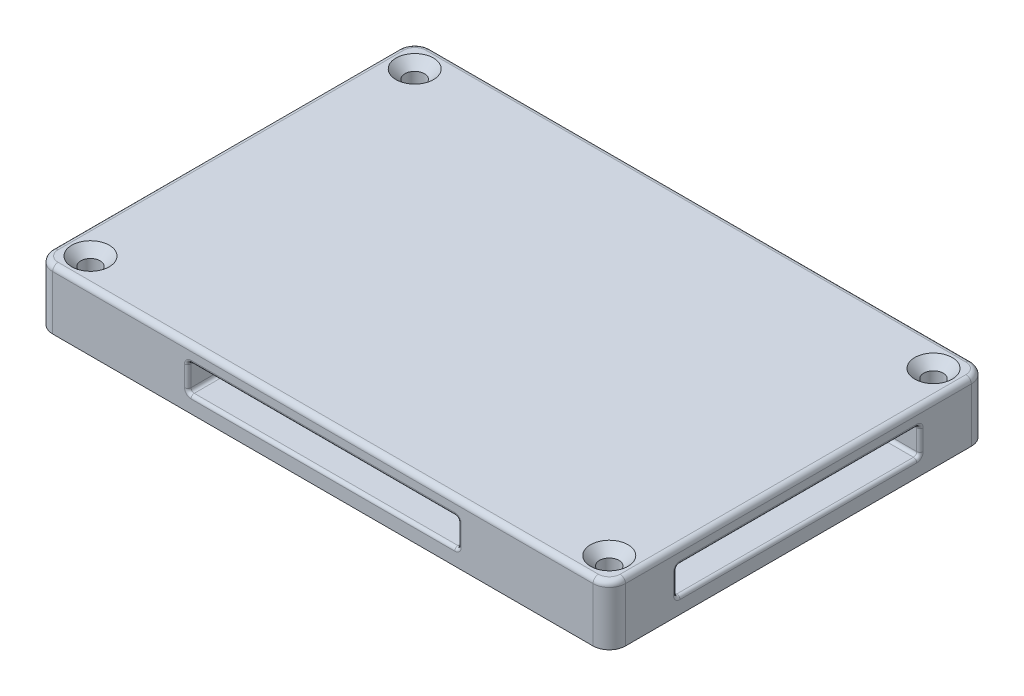
SolidWorks part; units mm, degrees
ref_plane "Alzado" through (0, 0, 0) normal (0, 0, 1) x (1, 0, 0)
ref_plane "Planta" through (0, 0, 0) normal (0, 1, 0) x (1, 0, 0)
ref_plane "Vista lateral" through (0, 0, 0) normal (1, 0, 0) x (0, 0, -1)
sketch "Croquis1" plane through (0, 0, 0) normal (0, 1, 0) x (1, 0, 0)
  line L1 (0, 0) -> (106, 0)
  line L2 (0, 0) -> (0, 70)
  line L3 (0, 70) -> (106, 70)
  line L4 (106, 0) -> (106, 70)
  dimension "D1" = 106
  dimension "D2" = 70
extrude "Saliente-Extruir1" add sketch "Croquis1" along normal blind 11
sketch "Croquis2" plane through (0, 0, 0) normal (0, 0, 1) x (1, 0, 0)
  line L0 (0, 0) -> (0, 3) construction
  line L1 (0, 11) -> (0, 0) construction
  line L2 (0, 3) -> (28, 3) construction
  line L4 (28, 3) -> (78, 3)
  line L5 (28, 3) -> (28, 8)
  line L6 (28, 8) -> (78, 8)
  line L7 (78, 3) -> (78, 8)
  dimension "D1" = 3
  dimension "D2" = 28
  dimension "D3" = 50
  dimension "D4" = 5
extrude "Cortar-Extruir1" cut sketch "Croquis2" against normal through all
sketch "Croquis3" plane through (106, 0, 0) normal (1, 0, 0) x (0, 0, -1)
  line L0 (0, 0) -> (0, 3) construction
  line L1 (0, 3) -> (12.5, 3) construction
  line L3 (12.5, 3) -> (57.5, 3)
  line L4 (12.5, 3) -> (12.5, 8)
  line L5 (12.5, 8) -> (57.5, 8)
  line L6 (57.5, 3) -> (57.5, 8)
  dimension "D1" = 45
  dimension "D2" = 12.5
  dimension "D3" = 5
extrude "Cortar-Extruir2" cut sketch "Croquis3" against normal through all
fillet "Redondeo1" radius 3 4 edges at (0, 5.5, 0) (0, 5.5, -70) (106, 5.5, -70) (106, 5.5, 0)
sketch "Croquis5" plane through (0, 11, 0) normal (0, 1, 0) x (1, 0, 0)
  line L0 (5, 0) -> (5, 5) construction
  line L1 (3, 0) -> (103, 0) construction
  line L2 (5, 5) -> (0, 5) construction
  line L3 (0, 67) -> (0, 3) construction
  line L4 (53, 0) -> (53, 70) construction
  line L5 (103, 70) -> (3, 70) construction
  line L6 (0, 35) -> (106, 35) construction
  line L7 (106, 3) -> (106, 67) construction
  point P15 (101, 5)
  point P16 (5, 5)
  point P17 (101, 65)
  point P18 (5, 65)
  dimension "D1" = 5
  dimension "D2" = 5
hole_wizard "Avellanado para tornillo con cabeza avellanada de clavija hexagonal de M32" positions "Croquis11" profile "Croquis12" countersink size "M3" standard "DIN" end condition through all
sketch "Croquis11" plane through (0, 11, 0) normal (0, 1, 0) x (1, 0, 0)
  point P0 (5, 65)
  point P3 (101, 65)
  point P6 (101, 5)
  point P9 (5, 5)
sketch "Croquis12" plane through (5, 11, -65) normal (1, 0, 0) x (0, 0, 1)
  line L0 (0, 0) -> (0, 11)
  line L1 (0, 11) -> (1.8, 11)
  line L2 (1.8, 11) -> (1.8, 1.67)
  line L3 (1.8, 1.67) -> (3.47, 0)
  line L5 (3.47, 0) -> (0, 0)
  line L6 (-1.8, 1.67) -> (-3.47, 0) construction
  line L11 (0, -6.35) -> (0, 107.95) construction
  dimension "Diámetro de taladro hasta el siguiente" = 3.6
  dimension "Profundidad de taladro hasta el siguiente" = 11
  dimension "Diámetro de avellanado cercano" = 6.94
  dimension "Ángulo de avellanado cercano" = 90
fillet "Redondeo2" radius 1 8 edges at (105.1213, 11, -0.8787) (53, 11, 0) (0.8787, 11, -0.8787) (0, 11, -35) (0.8787, 11, -69.1213) (53, 11, -70) (105.1213, 11, -69.1213) (106, 11, -35)
fillet "Redondeo3" radius 0.6 36 edges at (28, 5.5, 0) (78, 5.5, 0) (0, 5.5, -57.5) (106, 5.5, -57.5) (28, 5.5, -70) (28, 5.5, -57.5) (28, 5.5, -12.5) (0, 5.5, -12.5) (78, 5.5, -12.5) (106, 5.5, -12.5) (78, 5.5, -70) (78, 5.5, -57.5) (53, 8, 0) (78, 8, -6.25) (92, 8, -12.5) (106, 8, -35) (92, 8, -57.5) (78, 8, -63.75) (53, 8, -70) (28, 8, -63.75) (14, 8, -57.5) (0, 8, -35) (14, 8, -12.5) (28, 8, -6.25) (53, 3, 0) (28, 3, -6.25) (14, 3, -12.5) (0, 3, -35) (14, 3, -57.5) (28, 3, -63.75) (53, 3, -70) (78, 3, -63.75) (92, 3, -57.5) (106, 3, -35) (92, 3, -12.5) (78, 3, -6.25)
